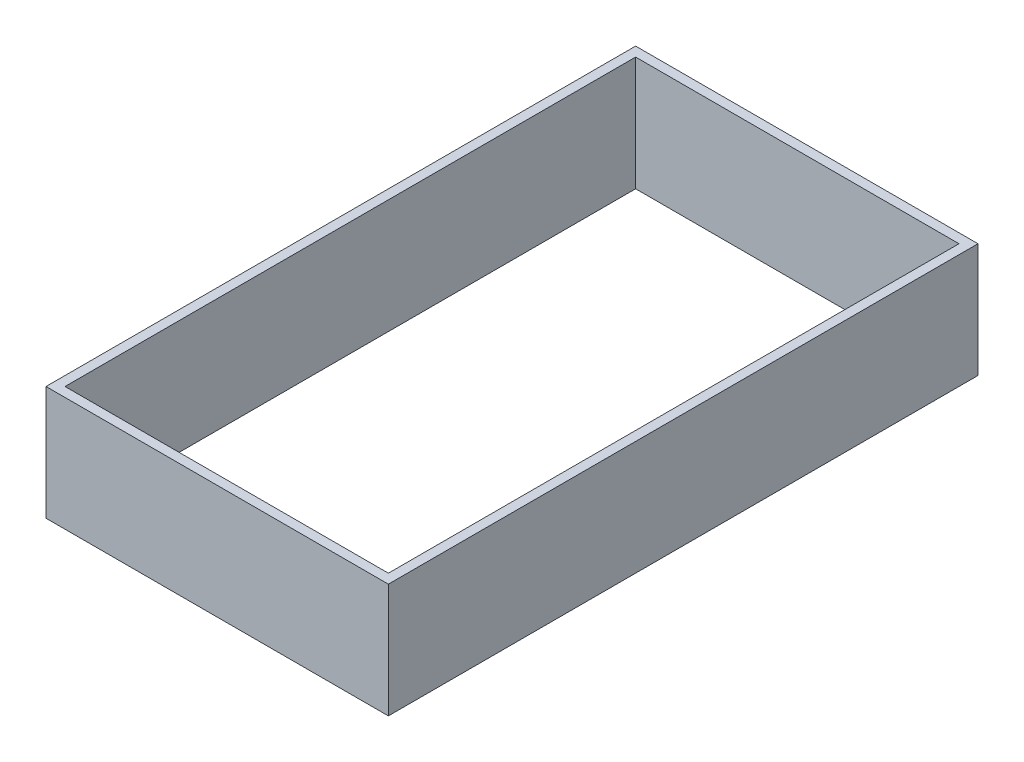
SolidWorks part; units mm, degrees
ref_plane "Front Plane" through (0, 0, 0) normal (0, 0, 1) x (1, 0, 0)
ref_plane "Top Plane" through (0, 0, 0) normal (0, 1, 0) x (1, 0, 0)
ref_plane "Right Plane" through (0, 0, 0) normal (1, 0, 0) x (0, 0, -1)
sketch "Sketch1" plane through (0, 0, 0) normal (0, 1, 0) x (1, 0, 0)
  line L1 (-9000, 15500) -> (9000, 15500)
  line L2 (-9000, 15500) -> (-9000, 15000)
  line L3 (-9000, 15000) -> (9000, 15000)
  line L4 (9000, 15500) -> (9000, 15000)
  line L5 (-9000, 15000) -> (-8500, 15000)
  line L6 (-9000, 15000) -> (-9000, -15000)
  line L7 (-9000, -15000) -> (-8500, -15000)
  line L8 (-8500, 15000) -> (-8500, -15000)
  line L9 (8500, 15000) -> (9000, 15000)
  line L10 (8500, 15000) -> (8500, -15000)
  line L11 (8500, -15000) -> (9000, -15000)
  line L12 (9000, 15000) -> (9000, -15000)
  line L13 (-9000, -15000) -> (9000, -15000)
  line L14 (-9000, -15000) -> (-9000, -15500)
  line L15 (-9000, -15500) -> (9000, -15500)
  line L16 (9000, -15000) -> (9000, -15500)
  point P16 (9000, -15250)
  dimension "D1" = 30000
  dimension "D2" = 17000
  dimension "D3" = 0
  dimension "D4" = 0
  dimension "D5" = 0
  dimension "D6" = 0
  dimension "D7" = 500
  dimension "D8" = 500
  dimension "D9" = 500
  dimension "D10" = 500
  dimension "D11" = 0
extrude "Boss-Extrude2" add sketch "Sketch1" along normal blind 6000 contours L8 L7 L6 L5 | L15 L16 L13 L14 | L10 L11 L12 L9 | L1 L4 L3 L2
sketch "Sketch2" plane through (0, 0, 15500) normal (0, 0, 1) x (1, 0, 0)
  line L1 (-9000, 0) -> (9000, 0)
  line L2 (-9000, 0) -> (-9000, -500)
  line L3 (-9000, -500) -> (9000, -500)
  line L4 (9000, 0) -> (9000, -500)
  dimension "D1" = 500
